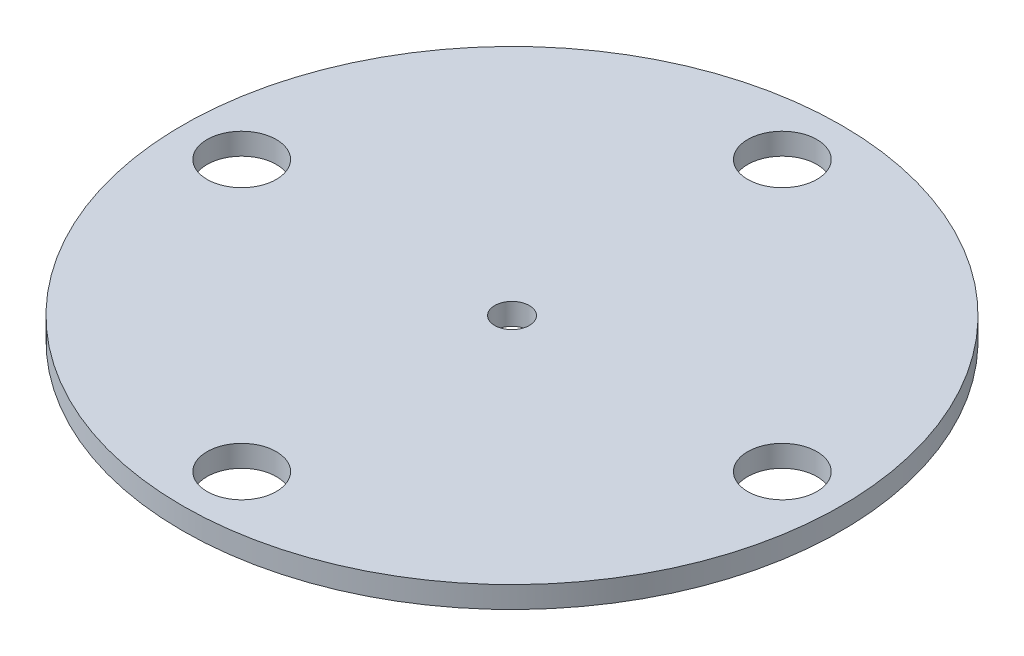
SolidWorks part; units mm, degrees
material "1060 Alloy"
ref_plane "Front Plane" through (0, 0, 0) normal (0, 0, 1) x (1, 0, 0)
ref_plane "Top Plane" through (0, 0, 0) normal (0, 1, 0) x (1, 0, 0)
ref_plane "Right Plane" through (0, 0, 0) normal (1, 0, 0) x (0, 0, -1)
sketch "Sketch1" plane through (0, 0, 0) normal (0, 1, 0) x (1, 0, 0)
  circle A0 centre (0, 0) radius 76.2
  circle A1 centre (0, 0) radius 4
  dimension "D1" = 152.4
  dimension "D2" = 8
extrude "Boss-Extrude2" add sketch "Sketch1" along normal blind 5 contours A0 A1
sketch "Sketch2" plane through (0, 5, 0) normal (0, 1, 0) x (1, 0, 0)
  circle A0 centre (0, 0) radius 62.5 construction
  circle A1 centre (0, -62.5) radius 8
  circle A2 centre (-62.5, 0) radius 8
  circle A3 centre (0, 62.5) radius 8
  circle A4 centre (62.5, 0) radius 8
  point P14 (0, 0)
  dimension "D1" = 125
  dimension "D2" = 16
  dimension "D3" = 4
extrude "Cut-Extrude1" cut sketch "Sketch2" against normal through all
